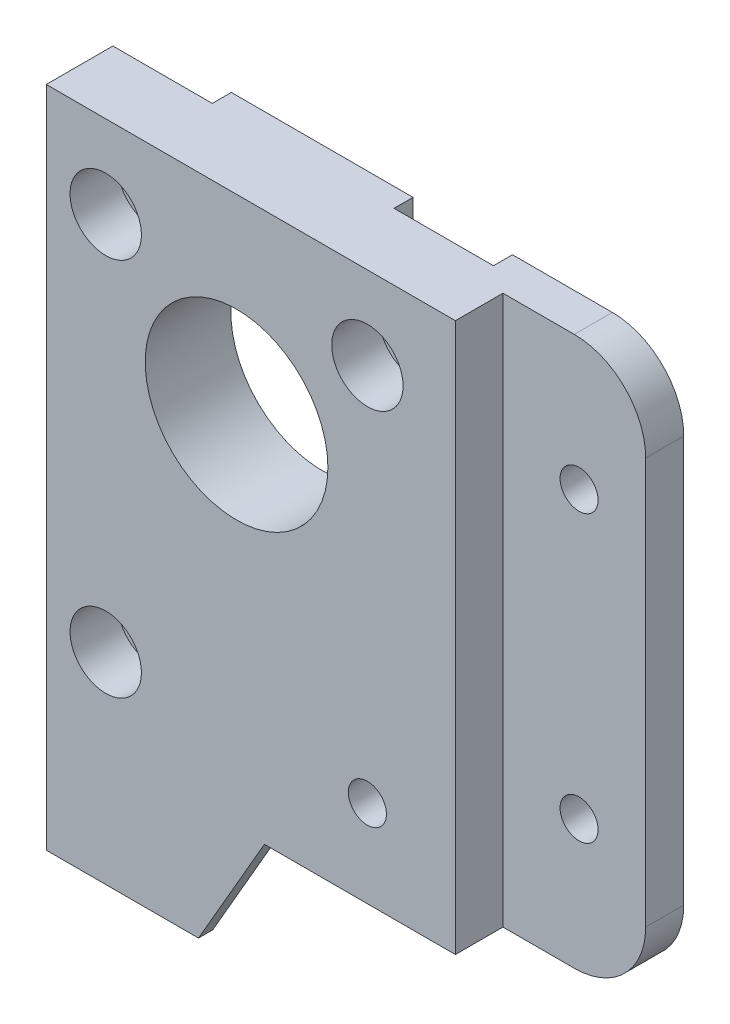
SolidWorks part; units mm, degrees
material "1060 Alloy"
ref_plane "Front Plane" through (0, 0, 0) normal (0, 0, 1) x (1, 0, 0)
ref_plane "Top Plane" through (0, 0, 0) normal (0, 1, 0) x (1, 0, 0)
ref_plane "Right Plane" through (0, 0, 0) normal (1, 0, 0) x (0, 0, -1)
sketch "Sketch1" plane through (0, 0, 0) normal (0, 0, 1) x (1, 0, 0)
  line L0 (-13.75, -19.7) -> (-9.788, -16.65) construction
  line L3 (20, 28.85) -> (38, 28.85)
  line L8 (20, -28.85) -> (-20, -28.85)
  line L9 (20, -28.85) -> (20, 28.85) construction
  line L10 (38, 28.85) -> (38, -28.85)
  line L11 (20, 28.85) -> (-20, 28.85)
  line L14 (-20, -28.85) -> (-20, 28.85)
  line L15 (20, -28.85) -> (-20, 28.85) construction
  line L16 (20, 28.85) -> (-20, -28.85) construction
  line L17 (-16.312, -16.3719) -> (-12.35, -13.3219)
  line L18 (-11.188, -23.0281) -> (-7.226, -19.9781)
  line L19 (0, -28.85) -> (0, 28.85) construction
  line L22 (38, -28.85) -> (20, -28.85)
  line L23 (17.2017, -17.3071) -> (20, -21.3437)
  line L24 (9.55, -19.7) -> (9.55, -28.85)
  line L25 (-9.55, 20.15) -> (-9.55, 28.85)
  line L26 (-17.2017, 17.7571) -> (-20, 21.7937)
  line L27 (9.55, 20.15) -> (9.55, 28.85)
  line L28 (17.2017, 17.7571) -> (20, 21.7937)
  line L29 (20, 21.7937) -> (20, 28.85)
  line L30 (-16.312, -16.3719) -> (-20, -16.3719)
  line L31 (20, -28.85) -> (20, -21.3437)
  line L32 (-20, -23.9) -> (-13.75, -23.9)
  circle A18 centre (-13.75, 20.15) radius 4.2
  circle A19 centre (13.75, 20.15) radius 4.2
  circle A20 centre (13.75, -19.7) radius 4.2
  arc A21 (-16.312, -16.3719) -> (-11.188, -23.0281) centre (-13.75, -19.7) ccw
  arc A22 (-7.226, -19.9781) -> (-12.35, -13.3219) centre (-9.788, -16.65) ccw
  circle A23 centre (0, 8.8) radius 9.6
  circle A24 centre (-5.725, -6.1) radius 4.2
  circle A25 centre (5.725, -6.1) radius 4.2
  point P0 (0, 0)
  point P14 (-6.4599, -14.088)
  point P31 (-11.769, -18.175)
  point P37 (5.725, -10.3)
  point P43 (20, 28.85)
  point P46 (-20, 28.85)
  dimension "D1" = 57.7
  dimension "D2" = 40
  dimension "D3" = 12.2
  dimension "D4" = 8.4
  dimension "D5" = 8.4
  dimension "D6" = 19.2
  dimension "D7" = 9.15
  dimension "D8" = 27.5
  dimension "D9" = 39.85
  dimension "D10" = 5
  dimension "D12" = 20.05
  dimension "D13" = 11.45
  dimension "D14" = 22.75
  dimension "D15" = 18
extrude "Boss-Extrude1" add sketch "Sketch1" along normal blind 2
sketch "Sketch4" plane through (0, 0, 2) normal (0, 0, 1) x (1, 0, 0)
  line L0 (0, -28.85) -> (0, 29) construction
  line L6 (38, -28.85) -> (20, -28.85) construction
  line L8 (-20, -28.85) -> (38, -28.85)
  line L11 (38, -28.85) -> (38, 28.85)
  line L12 (-20, 28.85) -> (-20, -28.85)
  line L13 (-20, -16.3719) -> (-20, 21.7937) construction
  line L14 (-20, 28.85) -> (38, 28.85)
  line L15 (20, 28.85) -> (38, 28.85) construction
  line L16 (38, 28.85) -> (38, -28.85) construction
  circle A2 centre (13.75, -19.7) radius 2
  circle A3 centre (-13.75, 20.15) radius 2
  circle A4 centre (13.75, 20.15) radius 2
  circle A10 centre (-13.75, -19.7) radius 2
  circle A11 centre (0, 8.8) radius 9.6
  circle A12 centre (0, 8.8) radius 9.6 construction
  dimension "D1" = 4
extrude "Boss-Extrude3" add sketch "Sketch4" along normal blind 2
sketch "Sketch5" plane through (0, 0, 4) normal (0, 0, 1) x (1, 0, 0)
  line L0 (-20, 0) -> (38, 0) construction
  line L3 (-20, 28.85) -> (-20, -28.85) construction
  line L4 (38, -28.85) -> (38, 28.85) construction
  circle A0 centre (31, 15) radius 2
  circle A1 centre (31, -15) radius 2
  dimension "D1" = 4
  dimension "D2" = 15
  dimension "D3" = 51
extrude "Cut-Extrude1" cut sketch "Sketch5" against normal blind 4
ref_plane "Plane1" through (0, 0, 0) normal (0, 0, -1) x (-1, 0, 0)
sketch "Sketch6" plane through (0, 0, 4) normal (0, 0, 1) x (1, 0, 0)
  line L0 (23, 28.85) -> (23, -28.85)
  line L1 (38, 28.85) -> (-20, 28.85) construction
  line L2 (-20, -28.85) -> (38, -28.85) construction
  line L3 (38, -28.85) -> (38, 28.85) construction
  circle A52 centre (-13.75, 20.15) radius 3.75
  circle A53 centre (13.75, 20.15) radius 3.75
  circle A54 centre (31, 15) radius 2
  circle A55 centre (13.75, -19.7) radius 3.75
  circle A56 centre (-13.75, -19.7) radius 3.75
  circle A57 centre (31, -15) radius 2
  circle A59 centre (31, 15) radius 2 construction
  circle A60 centre (31, -15) radius 2 construction
  line M5 (-20, 28.85) -> (-20, -28.85)
  line M6 (-20, -28.85) -> (38, -28.85)
  line M7 (38, -28.85) -> (38, 28.85)
  line M8 (38, 28.85) -> (-20, 28.85)
  circle M9 centre (13.75, -19.7) radius 2
  circle M11 centre (0, 8.8) radius 9.6
  dimension "D1" = 7.5
  dimension "D2" = 15
extrude "Boss-Extrude4" add sketch "Sketch6" along normal blind 5 contours A57 A56 A55 A54 A53 A52 M8 M5 M6 M7 M11 | A55 M9
sketch "Sketch7" plane through (0, 0, 4) normal (0, 0, 1) x (1, 0, 0)
  line L0 (38, -28.85) -> (38, 28.85) construction
  line L1 (30.5, 28.85) -> (38, 28.85)
  line L2 (38, 28.85) -> (38, 21.35)
  line L3 (-20, 0) -> (38, 0) construction
  line L4 (-20, 28.85) -> (-20, -28.85) construction
  line L5 (38, -28.85) -> (38, -21.35)
  line L6 (30.5, -28.85) -> (38, -28.85)
  arc A0 (38, 21.35) -> (30.5, 28.85) centre (30.5, 21.35) ccw
  arc A1 (38, -21.35) -> (30.5, -28.85) centre (30.5, -21.35) cw
  dimension "D1" = 15
extrude "Cut-Extrude2" cut sketch "Sketch7" against normal through all
sketch "Sketch9" plane through (-20, 0, 0) normal (-1, 0, 0) x (0, 0, 1)
  line L0 (9, -28.85) -> (9, -40.85)
  line L2 (9, -40.85) -> (0, -40.85)
  line L3 (0, -40.85) -> (0, -35.15)
  line L4 (0, -35.15) -> (3, -35.15)
  line L5 (3, -35.15) -> (3, -28.85)
  line L6 (9, -28.85) -> (0, -28.85) construction
  line L7 (0, -28.85) -> (0, -23.9) construction
  line L9 (3, -28.85) -> (9, -28.85)
  dimension "D1" = 6
  dimension "D2" = 12
  dimension "D3" = 6.3
extrude "Boss-Extrude5" add sketch "Sketch9" against normal blind 6
sketch "Sketch10" plane through (0, 0, 9) normal (0, 0, 1) x (1, 0, 0)
  line L0 (-14, -40.85) -> (-4, -40.85)
  line L1 (-4, -40.85) -> (2.9282, -28.85)
  line L3 (2.9282, -28.85) -> (-14, -28.85)
  line L4 (-14, -28.85) -> (-14, -40.85)
  dimension "D1" = 10
  dimension "D2" = 120
extrude "Boss-Extrude6" add sketch "Sketch10" against normal blind 1.5
